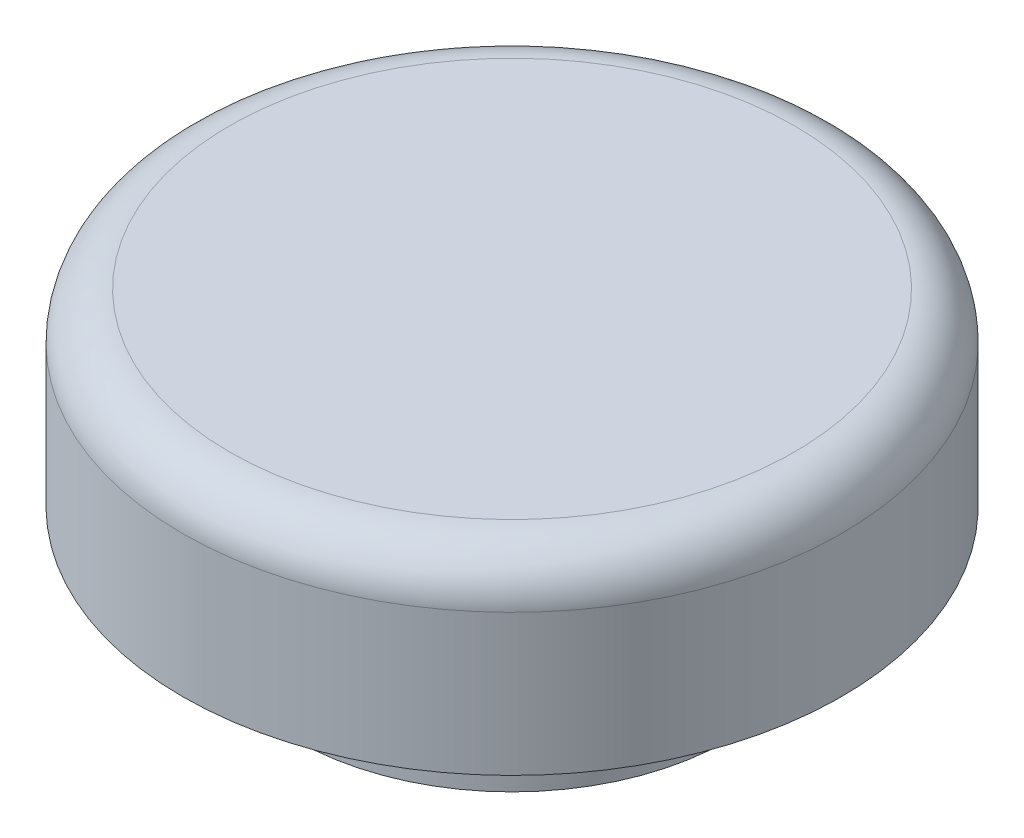
SolidWorks part; units mm, degrees
ref_plane "前视基准面" through (0, 0, 0) normal (0, 0, 1) x (1, 0, 0)
ref_plane "上视基准面" through (0, 0, 0) normal (0, 1, 0) x (1, 0, 0)
ref_plane "右视基准面" through (0, 0, 0) normal (1, 0, 0) x (0, 0, -1)
sketch "草图1" plane through (0, 0, 0) normal (0, 1, 0) x (1, 0, 0)
  circle A0 centre (0, 0) radius 2.3
  dimension "D1" = 4.6
extrude "凸台-拉伸1" add sketch "草图1" along normal blind 1
sketch "草图2" plane through (0, 1, 0) normal (0, 1, 0) x (1, 0, 0)
  circle A0 centre (0, 0) radius 3.5
  dimension "D1" = 7
extrude "凸台-拉伸2" add sketch "草图2" along normal blind 2 contours A0
fillet "圆角1" radius 0.5 1 edges at (0, 3, 3.5)
